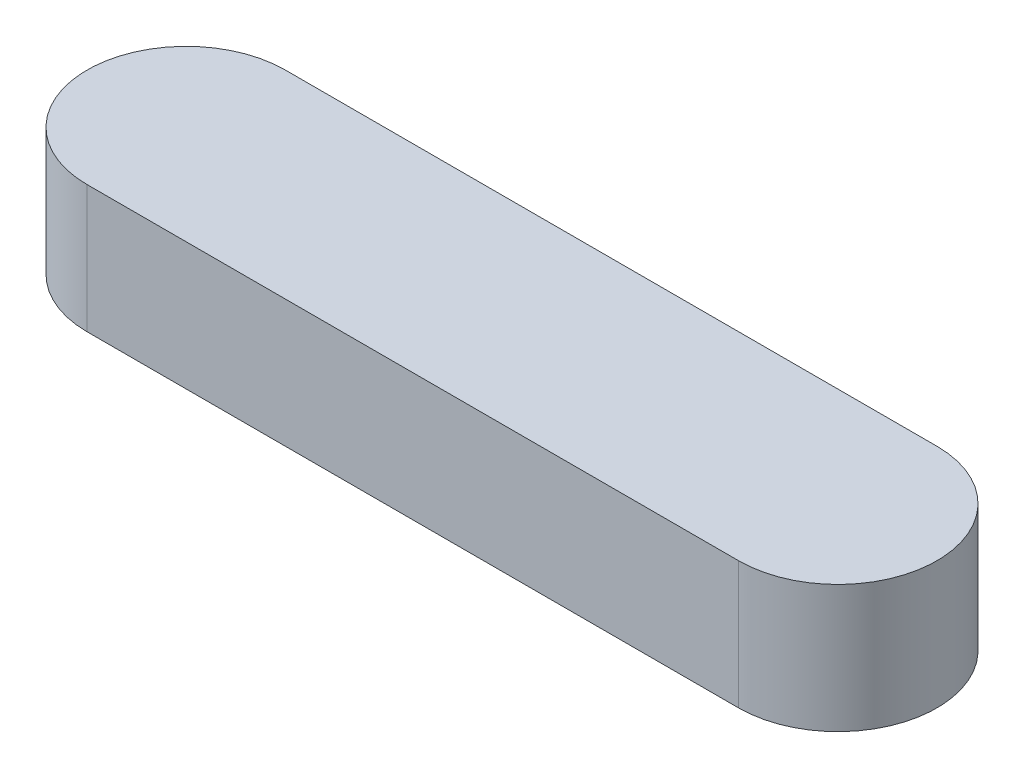
SolidWorks part; units mm, degrees
ref_plane "Спереди" through (0, 0, 0) normal (0, 0, 1) x (1, 0, 0)
ref_plane "Сверху" through (0, 0, 0) normal (0, 1, 0) x (1, 0, 0)
ref_plane "Справа" through (0, 0, 0) normal (1, 0, 0) x (0, 0, -1)
other "Configuration Table"
sketch "Эскиз1" plane through (0, 0, 0) normal (0, 1, 0) x (1, 0, 0)
  line L0 (-23, 0) -> (23, 0) construction
  line L1 (-23, 7) -> (23, 7)
  line L2 (-23, -7) -> (23, -7)
  arc A0 (-23, 7) -> (-23, -7) centre (-23, 0) ccw
  arc A1 (23, -7) -> (23, 7) centre (23, 0) ccw
  point P2 (0, 0)
  dimension "D1" = 60
  dimension "D2" = 7
  dimension "D3" = 14
extrude "Бобышка-Вытянуть1" add sketch "Эскиз1" along normal blind 9
